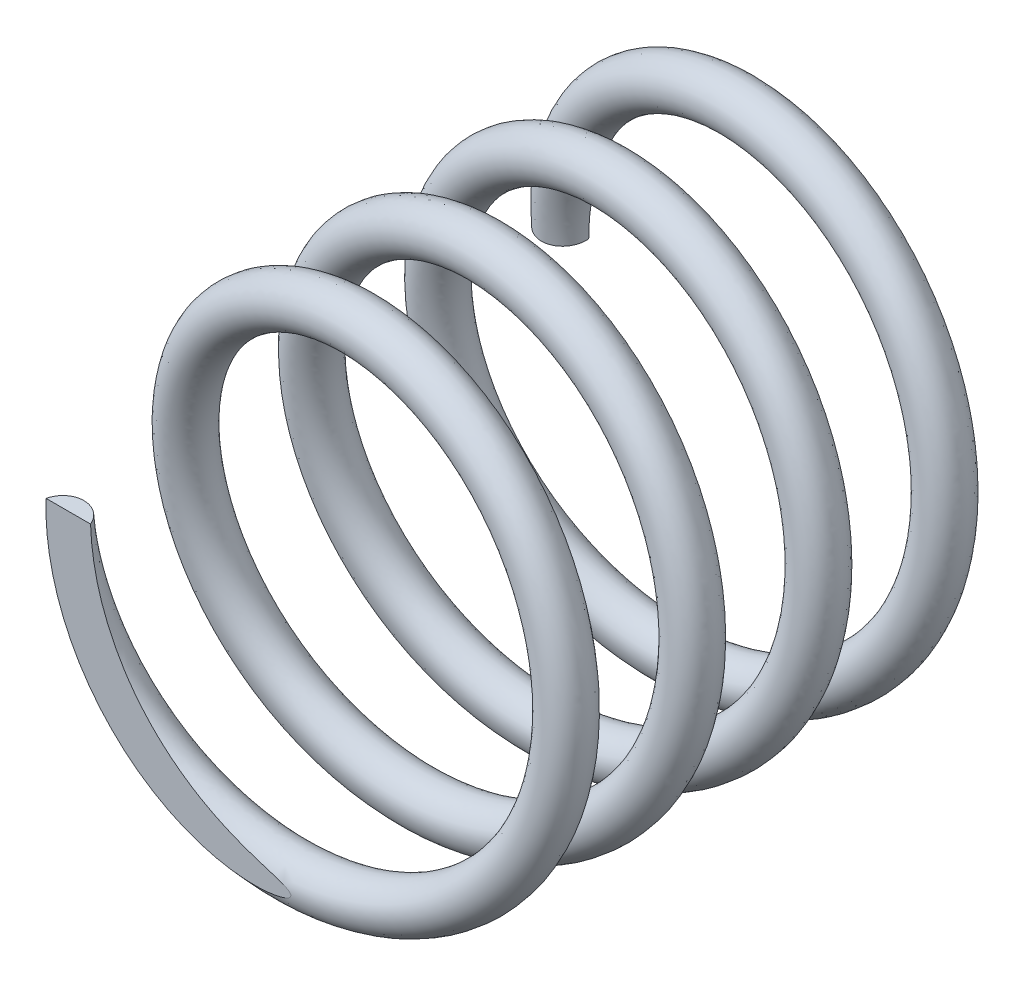
SolidWorks part; units mm, degrees
material "AISI 304"
ref_plane "Front Plane" through (0, 0, 0) normal (0, 0, 1) x (1, 0, 0)
ref_plane "Top Plane" through (0, 0, 0) normal (0, 1, 0) x (1, 0, 0)
ref_plane "Right Plane" through (0, 0, 0) normal (1, 0, 0) x (0, 0, -1)
sketch "Sketch1" plane through (0, 0, 0) normal (0, 0, 1) x (1, 0, 0)
  circle A0 centre (0, 0) radius 44.45
  circle A1 centre (0, 0) radius 50.8 construction
  dimension "D1" = 88.9
  dimension "D2" = 101.6
curve "Helix/Spiral1" pitch 25.4 height 101.6 turns 4
ref_plane "Plane1" through (-44.45, 0, 101.6) normal (0, 0.9959, 0.0906) x (-0.7602, -0.0588, 0.647)
sketch "Sketch2" plane through (-44.45, 0, 101.6) normal (0, 0.9959, 0.0906) x (-0.7602, -0.0588, 0.647)
  circle A0 centre (0, 0) radius 4.7625
  dimension "D1" = 9.525
sweep "Sweep1" add profiles "Sketch2" path "Helix/Spiral1"
ref_plane "Plane2" through (0, 0, 0) normal (0, 0, 1) x (1, 0, 0)
other "SurfaceCut1"
ref_plane "Plane4" through (0, 0, 100) normal (0, 0, 1) x (1, 0, 0)
other "SurfaceCut3"
